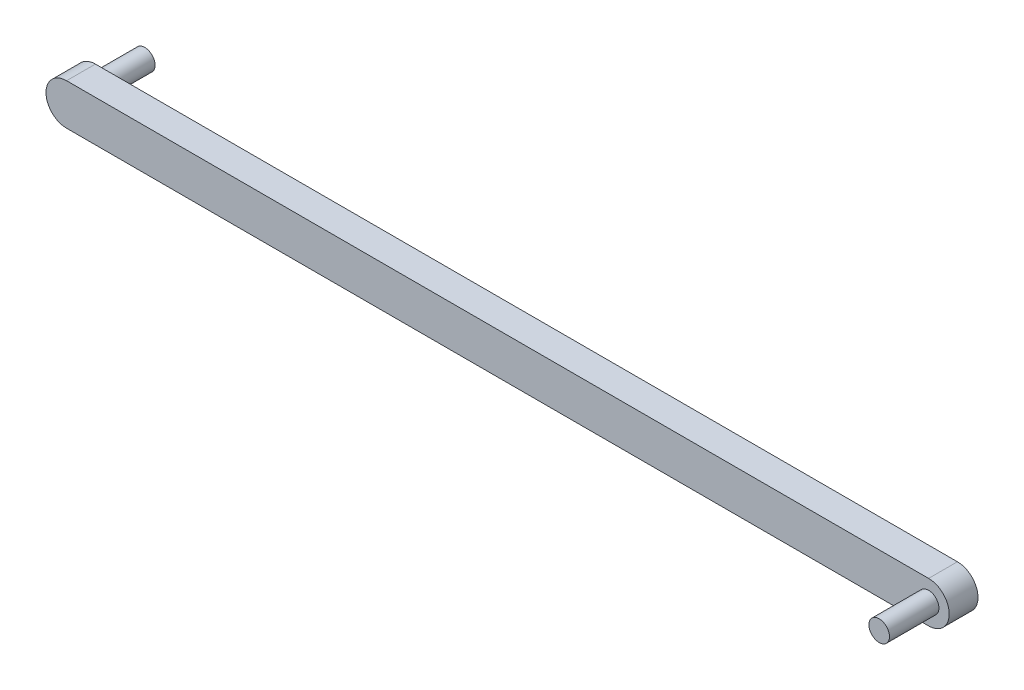
SolidWorks part; units mm, degrees
ref_plane "Front Plane" through (0, 0, 0) normal (0, 0, 1) x (1, 0, 0)
ref_plane "Top Plane" through (0, 0, 0) normal (0, 1, 0) x (1, 0, 0)
ref_plane "Right Plane" through (0, 0, 0) normal (1, 0, 0) x (0, 0, -1)
sketch "Sketch1" plane through (0, 0, 0) normal (0, 0, 1) x (1, 0, 0)
  line L0 (-52.349, 0) -> (52.349, 0) construction
  line L1 (-52.349, 2.5) -> (52.349, 2.5)
  line L2 (-52.349, -2.5) -> (52.349, -2.5)
  arc A0 (-52.349, 2.5) -> (-52.349, -2.5) centre (-52.349, 0) ccw
  arc A1 (52.349, -2.5) -> (52.349, 2.5) centre (52.349, 0) ccw
  point P2 (0, 0)
  dimension "D2" = 2.5
  dimension "D1" = 104.698
extrude "Boss-Extrude1" add sketch "Sketch1" along normal blind 3.5
sketch "Sketch2" plane through (0, 0, 3.5) normal (0, 0, 1) x (1, 0, 0)
  circle A0 centre (52.349, 0) radius 1.25
  dimension "D1" = 2.5
extrude "Boss-Extrude2" add sketch "Sketch2" along normal blind 6
sketch "Sketch3" plane through (0, 0, 0) normal (0, 0, -1) x (-1, 0, 0)
  circle A0 centre (52.349, 0) radius 1.25
  circle A1 centre (-52.349, 0) radius 1.25 construction
extrude "Boss-Extrude3" add sketch "Sketch3" along normal blind 6
